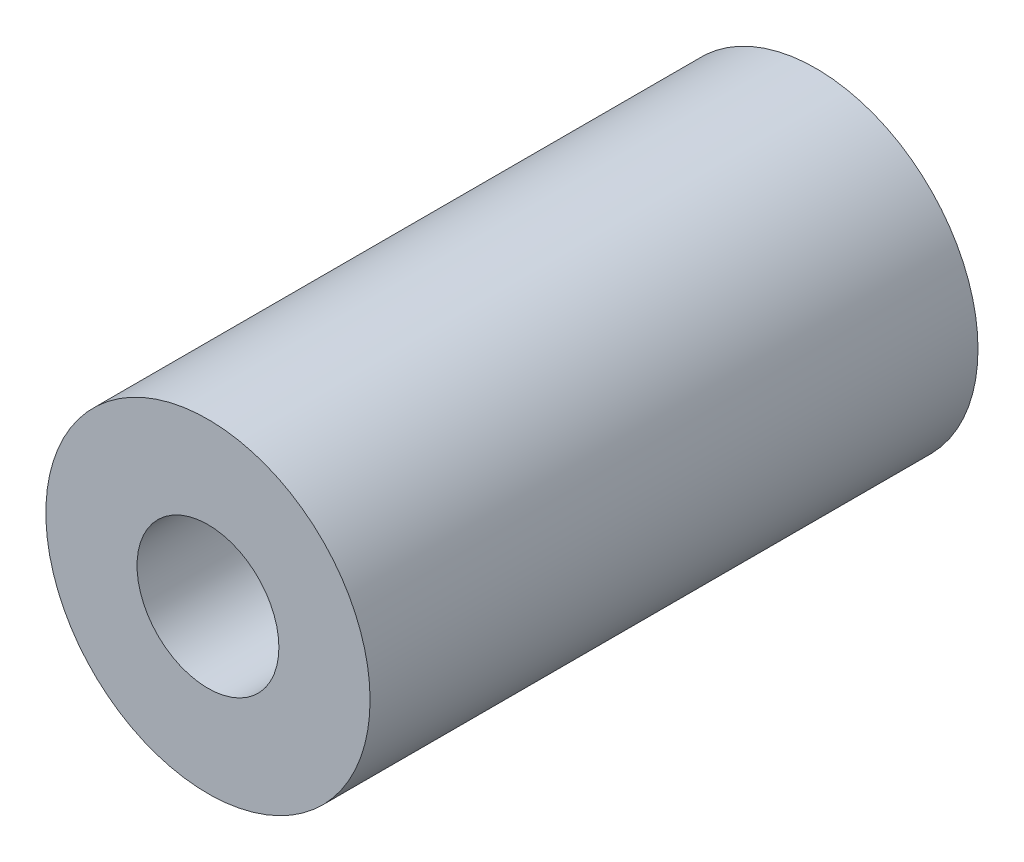
SolidWorks part; units mm, degrees
ref_plane "Plan de face" through (0, 0, 0) normal (0, 0, 1) x (1, 0, 0)
ref_plane "Plan de dessus" through (0, 0, 0) normal (0, 1, 0) x (1, 0, 0)
ref_plane "Plan de droite" through (0, 0, 0) normal (1, 0, 0) x (0, 0, -1)
sketch "Esquisse1" plane through (0, 0, 0) normal (0, 0, 1) x (1, 0, 0)
  line L1 (-4, 4) -> (4, 4) construction
  line L2 (-4, 4) -> (-4, -4) construction
  line L3 (-4, -4) -> (4, -4) construction
  line L4 (4, 4) -> (4, -4) construction
  line L5 (-4, 4) -> (4, -4) construction
  line L6 (-4, -4) -> (4, 4) construction
  circle A0 centre (0, 0) radius 1.75
  circle A1 centre (0, 0) radius 4
  point P0 (0, 0)
  dimension "D1" = 3.5
  dimension "D2" = 8
extrude "Boss.-Extru.1" add sketch "Esquisse1" along normal mid plane 15
